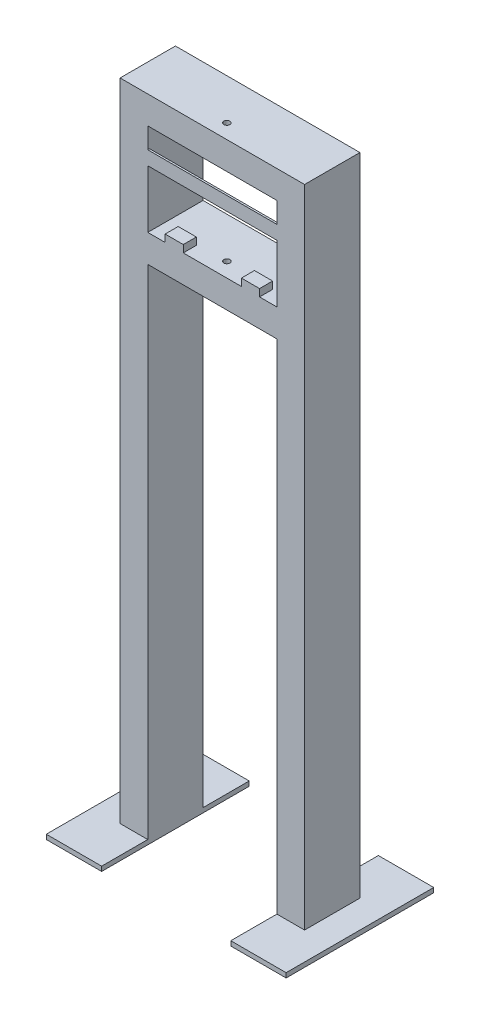
SolidWorks part; units mm, degrees
ref_plane "Front Plane" through (0, 0, 0) normal (0, 0, 1) x (1, 0, 0)
ref_plane "Top Plane" through (0, 0, 0) normal (0, 1, 0) x (1, 0, 0)
ref_plane "Right Plane" through (0, 0, 0) normal (1, 0, 0) x (0, 0, -1)
sketch "Sketch1" plane through (0, 0, 0) normal (0, 1, 0) x (1, 0, 0)
  line L0 (0, 0) -> (0, -375.7127) construction
  line L1 (165.1, 0) -> (165.1, -203.2)
  line L2 (-88.9, 0) -> (-165.1, 0)
  line L3 (-88.9, 0) -> (-88.9, -203.2)
  line L4 (-88.9, -203.2) -> (-165.1, -203.2)
  line L5 (-165.1, 0) -> (-165.1, -203.2)
  line L6 (88.9, -203.2) -> (165.1, -203.2)
  line L7 (88.9, 0) -> (165.1, 0)
  line L8 (88.9, 0) -> (88.9, -203.2)
  dimension "D1" = 203.2
  dimension "D2" = 76.2
  dimension "D3" = 177.8
extrude "Boss-Extrude1" add sketch "Sketch1" along normal blind 6.35
sketch "Sketch2" plane through (0, 6.35, 0) normal (0, 1, 0) x (1, 0, 0)
  line L0 (-165.1, -101.6) -> (165.1, -101.6) construction
  line L1 (-165.1, 0) -> (-165.1, -203.2) construction
  line L2 (165.1, -203.2) -> (165.1, 0) construction
  line L3 (0, -57.8044) -> (0, -151.3067) construction
  line L4 (-88.9, -203.2) -> (-88.9, 0) construction
  line L5 (-127, -139.7) -> (-88.9, -139.7)
  line L6 (-127, -139.7) -> (-127, -63.5)
  line L7 (-127, -63.5) -> (-88.9, -63.5)
  line L8 (-88.9, -139.7) -> (-88.9, -63.5)
  line L9 (-127, -139.7) -> (-88.9, -63.5) construction
  line L10 (-127, -63.5) -> (-88.9, -139.7) construction
  line L11 (127, -139.7) -> (127, -63.5)
  line L12 (127, -139.7) -> (88.9, -139.7)
  line L13 (88.9, -139.7) -> (88.9, -63.5)
  line L14 (127, -63.5) -> (88.9, -63.5)
  point P9 (-107.95, -101.6)
  dimension "D1" = 76.2
  dimension "D2" = 38.1
extrude "Boss-Extrude2" add sketch "Sketch2" along normal blind 889
sketch "Sketch3" plane through (0, 0, 139.7) normal (0, 0, 1) x (1, 0, 0)
  line L0 (88.9, 895.35) -> (88.9, 6.35) construction
  line L1 (-88.9, 895.35) -> (88.9, 895.35)
  line L2 (-88.9, 895.35) -> (-88.9, 857.25)
  line L3 (-88.9, 857.25) -> (88.9, 857.25)
  line L4 (88.9, 895.35) -> (88.9, 857.25)
  line L5 (-88.9, 895.35) -> (-88.9, 6.35) construction
  line L6 (88.9, 730.25) -> (-88.9, 730.25)
  line L7 (88.9, 730.25) -> (88.9, 692.15)
  line L8 (88.9, 692.15) -> (-88.9, 692.15)
  line L9 (-88.9, 730.25) -> (-88.9, 692.15)
  dimension "D1" = 38.1
  dimension "D2" = 38.1
  dimension "D3" = 203.2
extrude "Boss-Extrude3" add sketch "Sketch3" against normal up to surface (76.2 mm away) up to face at (-107.95, 450.85, 63.5)
sketch "Sketch4" plane through (0, 895.35, 0) normal (0, 1, 0) x (1, 0, 0)
  line L0 (0, -139.7) -> (0, -63.5) construction
  line L1 (-127, -139.7) -> (127, -139.7) construction
  line L2 (127, -63.5) -> (-127, -63.5) construction
  circle A0 centre (0, -119.7) radius 4.2
  dimension "D1" = 8.4
  dimension "D2" = 20
extrude "Cut-Extrude1" cut sketch "Sketch4" against normal blind 180
sketch "Sketch5" plane through (0, 857.25, 0) normal (0, -1, 0) x (1, 0, 0)
  line L0 (0, 119.7) -> (0, 139.7) construction
  line L1 (-88.9, 139.7) -> (88.9, 139.7) construction
  line L2 (0, 119.7) -> (-24, 119.7) construction
  circle A0 centre (-12, 119.7) radius 2.6
  circle A1 centre (12, 119.7) radius 2.6
  dimension "D1" = 5.2
  dimension "D2" = 24
extrude "Cut-Extrude2" cut sketch "Sketch5" against normal blind 10
sketch "Sketch6" plane through (0, 730.25, 0) normal (0, 1, 0) x (1, 0, 0)
  line L0 (0, -139.7) -> (0, -97.6861) construction
  line L1 (88.9, -139.7) -> (-88.9, -139.7) construction
  line L2 (40, -139.7) -> (65, -139.7)
  line L3 (-40, -139.7) -> (-65, -139.7)
  line L4 (-40, -139.7) -> (-40, -121.7)
  line L5 (-40, -121.7) -> (-65, -121.7)
  line L6 (-65, -139.7) -> (-65, -121.7)
  line L7 (65, -139.7) -> (65, -121.7)
  line L8 (40, -121.7) -> (65, -121.7)
  line L9 (40, -139.7) -> (40, -121.7)
  dimension "D1" = 80
  dimension "D2" = 25
  dimension "D3" = 18
extrude "Boss-Extrude4" add sketch "Sketch6" along normal blind 10
sketch "Sketch7" plane through (0, 0, 139.7) normal (0, 0, 1) x (1, 0, 0)
  line L0 (-88.9, 857.25) -> (-88.9, 730.25) construction
  line L1 (-88.9, 828.75) -> (88.9, 828.75)
  line L2 (-88.9, 828.75) -> (-88.9, 809.75)
  line L3 (-88.9, 809.75) -> (88.9, 809.75)
  line L4 (88.9, 828.75) -> (88.9, 809.75)
  line L5 (88.9, 857.25) -> (88.9, 730.25) construction
  line L6 (-88.9, 857.25) -> (88.9, 857.25) construction
  point P8 (88.9, 819.25)
  dimension "D1" = 19
  dimension "D2" = 38
extrude "Boss-Extrude5" add sketch "Sketch7" against normal blind 2.54
